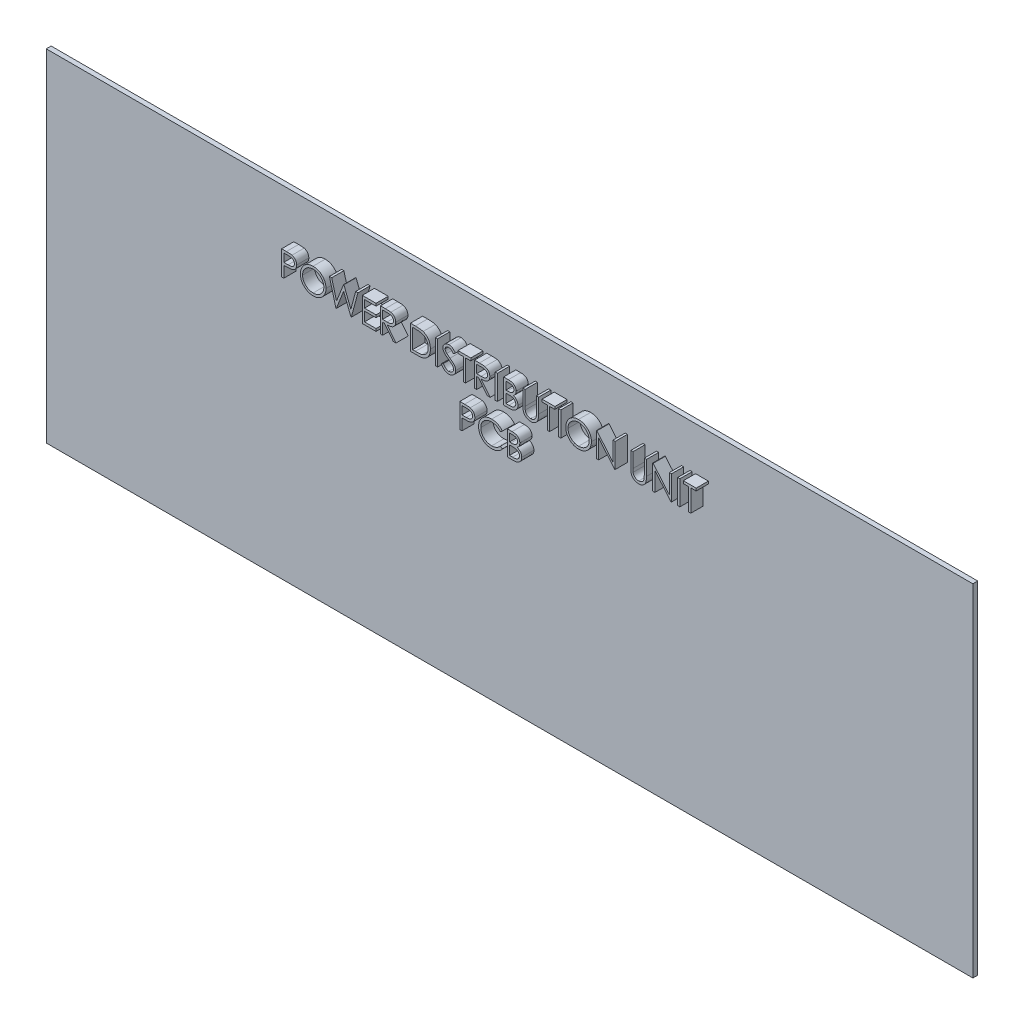
SolidWorks part; units mm, degrees
ref_plane "Front Plane" through (0, 0, 0) normal (0, 0, 1) x (1, 0, 0)
ref_plane "Top Plane" through (0, 0, 0) normal (0, 1, 0) x (1, 0, 0)
ref_plane "Right Plane" through (0, 0, 0) normal (1, 0, 0) x (0, 0, -1)
sketch "Sketch1" plane through (0, 0, 0) normal (0, 0, 1) x (1, 0, 0)
  line L1 (-190, -70) -> (190, -70)
  line L2 (-190, -70) -> (-190, 70)
  line L3 (-190, 70) -> (190, 70)
  line L4 (190, -70) -> (190, 70)
  line L5 (0, 70) -> (0, -70) construction
  line L6 (-190, 0) -> (190, 0) construction
  point P0 (0, 0)
  dimension "D1" = 140
  dimension "D2" = 380
extrude "Boss-Extrude1" add sketch "Sketch1" along normal blind 2
sketch "Sketch2" plane through (0, 0, 2) normal (0, 0, 1) x (1, 0, 0)
  text T0 "POWER DISTRIBUTION UNIT \r\n                   PCB" font "Century Gothic" height 10
extrude "Boss-Extrude2" add sketch "Sketch2" along normal blind 5
